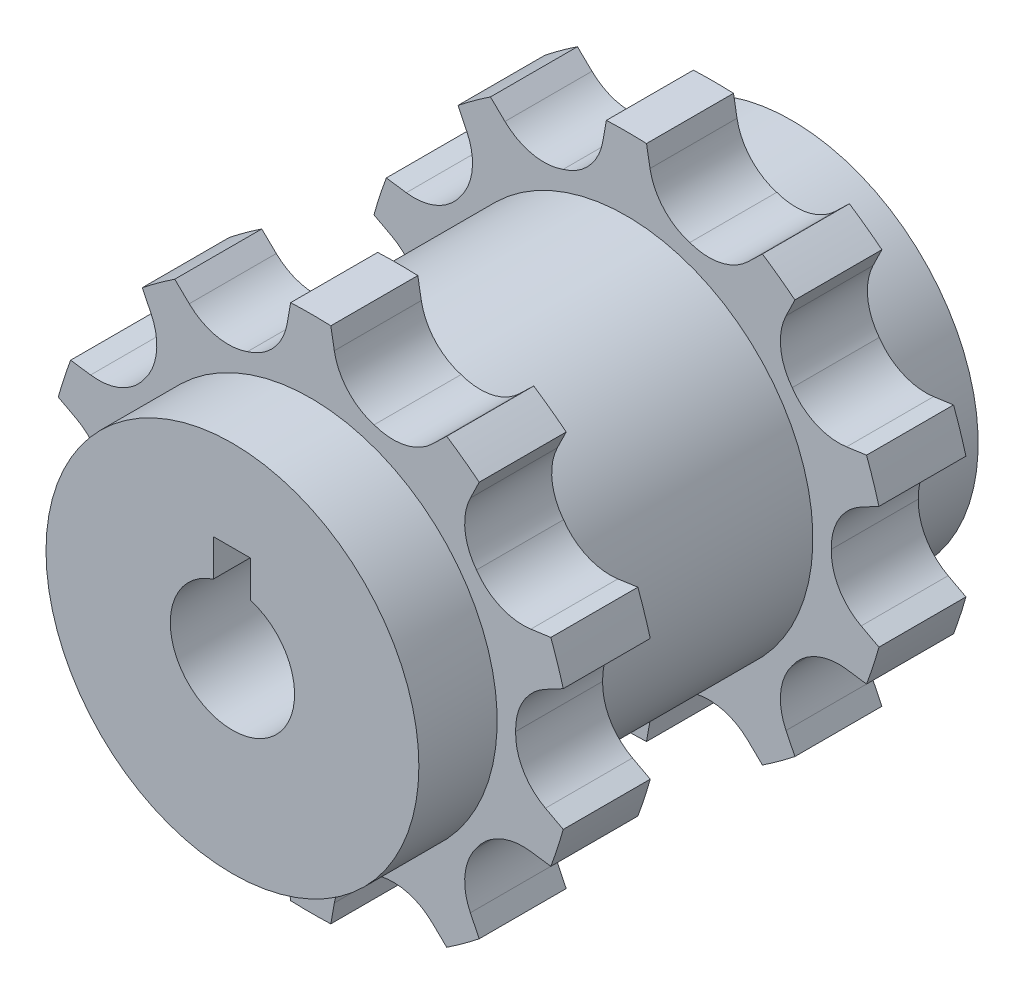
SolidWorks part; units mm, degrees
ref_plane "前视基准面" through (0, 0, 0) normal (0, 0, 1) x (1, 0, 0)
ref_plane "上视基准面" through (0, 0, 0) normal (0, 1, 0) x (1, 0, 0)
ref_plane "右视基准面" through (0, 0, 0) normal (1, 0, 0) x (0, 0, -1)
ref_plane "基准面4" through (0, 0, 28.9) normal (0, 0, 1) x (1, 0, 0)
sketch "草图1" plane through (0, 0, 28.9) normal (0, 0, 1) x (1, 0, 0)
  line L0 (42.4112, 45.7781) -> (42.1294, 47.3763)
  line L1 (38.8996, 47.3763) -> (38.6178, 45.7781)
  line L2 (30.741, 43.2187) -> (29.5736, 44.3461)
  line L3 (26.9607, 42.4477) -> (27.6721, 40.989)
  line L4 (22.804, 34.2886) -> (21.1969, 34.5145)
  line L5 (20.1988, 31.4428) -> (21.6317, 30.6809)
  line L6 (21.6317, 22.3988) -> (20.1988, 21.6369)
  line L7 (21.1969, 18.5652) -> (22.804, 18.791)
  line L8 (27.6721, 12.0906) -> (26.9607, 10.632)
  line L9 (29.5736, 8.7336) -> (30.741, 9.8609)
  line L10 (38.6178, 7.3016) -> (38.8996, 5.7034)
  line L11 (42.1294, 5.7034) -> (42.4112, 7.3016)
  line L12 (50.288, 9.8609) -> (51.4554, 8.7336)
  line L13 (54.0683, 10.632) -> (53.3569, 12.0906)
  line L14 (58.225, 18.791) -> (59.8321, 18.5652)
  line L15 (60.8302, 21.6369) -> (59.3973, 22.3988)
  line L16 (59.3973, 30.6809) -> (60.8302, 31.4428)
  line L17 (59.8321, 34.5145) -> (58.225, 34.2886)
  line L18 (53.3569, 40.989) -> (54.0683, 42.4477)
  line L19 (51.4554, 44.3461) -> (50.288, 43.2187)
  arc A0 (50.288, 43.2187) -> (45.609, 42.2191) centre (47.1467, 46.4716) cw
  arc A1 (45.609, 42.2191) -> (42.4112, 45.7781) centre (46.8645, 46.5633) cw
  arc A2 (42.1294, 47.3763) -> (38.8996, 47.3763) centre (40.5145, 8.5098) ccw
  arc A3 (38.6178, 45.7781) -> (35.42, 42.2191) centre (34.1645, 46.5633) cw
  arc A4 (35.42, 42.2191) -> (30.741, 43.2187) centre (33.8823, 46.4716) cw
  arc A5 (29.5736, 44.3461) -> (26.9607, 42.4477) centre (51.1123, 11.9533) ccw
  arc A6 (27.6721, 40.989) -> (27.1769, 36.2301) centre (23.6077, 39.0067) cw
  arc A7 (27.1769, 36.2301) -> (22.804, 34.2886) centre (23.4333, 38.7666) cw
  arc A8 (21.1969, 34.5145) -> (20.1988, 31.4428) centre (57.6621, 20.9683) ccw
  arc A9 (21.6317, 30.6809) -> (24.0284, 26.5398) centre (19.5088, 26.6882) cw
  arc A10 (24.0284, 26.5398) -> (21.6317, 22.3988) centre (19.5088, 26.3915) cw
  arc A11 (20.1988, 21.6369) -> (21.1969, 18.5652) centre (57.6621, 32.1114) ccw
  arc A12 (22.804, 18.791) -> (27.1769, 16.8495) centre (23.4333, 14.313) cw
  arc A13 (27.1769, 16.8495) -> (27.6721, 12.0906) centre (23.6077, 14.073) cw
  arc A14 (26.9607, 10.632) -> (29.5736, 8.7336) centre (51.1123, 41.1264) ccw
  arc A15 (30.741, 9.8609) -> (35.42, 10.8606) centre (33.8823, 6.6081) cw
  arc A16 (35.42, 10.8606) -> (38.6178, 7.3016) centre (34.1645, 6.5164) cw
  arc A17 (38.8996, 5.7034) -> (42.1294, 5.7034) centre (40.5145, 44.5698) ccw
  arc A18 (42.4112, 7.3016) -> (45.609, 10.8606) centre (46.8645, 6.5164) cw
  arc A19 (45.609, 10.8606) -> (50.288, 9.8609) centre (47.1467, 6.6081) cw
  arc A20 (51.4554, 8.7336) -> (54.0683, 10.632) centre (29.9167, 41.1264) ccw
  arc A21 (53.3569, 12.0906) -> (53.8521, 16.8495) centre (57.4213, 14.073) cw
  arc A22 (53.8521, 16.8495) -> (58.225, 18.791) centre (57.5957, 14.313) cw
  arc A23 (59.8321, 18.5652) -> (60.8302, 21.6369) centre (23.367, 32.1114) ccw
  arc A24 (59.3973, 22.3988) -> (57.0006, 26.5398) centre (61.5202, 26.3915) cw
  arc A25 (57.0006, 26.5398) -> (59.3973, 30.6809) centre (61.5202, 26.6882) cw
  arc A26 (60.8302, 31.4428) -> (59.8321, 34.5145) centre (23.367, 20.9683) ccw
  arc A27 (58.225, 34.2886) -> (53.8521, 36.2301) centre (57.5957, 38.7666) cw
  arc A28 (53.8521, 36.2301) -> (53.3569, 40.989) centre (57.4213, 39.0067) cw
  arc A29 (54.0683, 42.4477) -> (51.4554, 44.3461) centre (29.9167, 11.9533) ccw
extrude "凸台-拉伸1" add sketch "草图1" against normal blind 7
sketch "草图2" plane through (0, 0, 21.9) normal (0, 0, -1) x (-1, 0, 0)
  circle A0 centre (-40.5145, 26.5398) radius 15
extrude "凸台-拉伸2" add sketch "草图2" along normal blind 18.4
ref_plane "基准面5" through (0, 0, 3.5) normal (0, 0, 1) x (1, 0, 0)
sketch "草图3" plane through (0, 0, 3.5) normal (0, 0, 1) x (1, 0, 0)
  line L0 (42.4112, 45.7781) -> (42.1294, 47.3763)
  line L1 (38.8996, 47.3763) -> (38.6178, 45.7781)
  line L2 (30.741, 43.2187) -> (29.5736, 44.3461)
  line L3 (26.9607, 42.4477) -> (27.6721, 40.989)
  line L4 (22.804, 34.2886) -> (21.1969, 34.5145)
  line L5 (20.1988, 31.4428) -> (21.6317, 30.6809)
  line L6 (21.6317, 22.3988) -> (20.1988, 21.6369)
  line L7 (21.1969, 18.5652) -> (22.804, 18.791)
  line L8 (27.6721, 12.0906) -> (26.9607, 10.632)
  line L9 (29.5736, 8.7336) -> (30.741, 9.8609)
  line L10 (38.6178, 7.3016) -> (38.8996, 5.7034)
  line L11 (42.1294, 5.7034) -> (42.4112, 7.3016)
  line L12 (50.288, 9.8609) -> (51.4554, 8.7336)
  line L13 (54.0683, 10.632) -> (53.3569, 12.0906)
  line L14 (58.225, 18.791) -> (59.8321, 18.5652)
  line L15 (60.8302, 21.6369) -> (59.3973, 22.3988)
  line L16 (59.3973, 30.6809) -> (60.8302, 31.4428)
  line L17 (59.8321, 34.5145) -> (58.225, 34.2886)
  line L18 (53.3569, 40.989) -> (54.0683, 42.4477)
  line L19 (51.4554, 44.3461) -> (50.288, 43.2187)
  arc A0 (50.288, 43.2187) -> (45.609, 42.2191) centre (47.1467, 46.4716) cw
  arc A1 (45.609, 42.2191) -> (42.4112, 45.7781) centre (46.8645, 46.5633) cw
  arc A2 (42.1294, 47.3763) -> (38.8996, 47.3763) centre (40.5145, 8.5098) ccw
  arc A3 (38.6178, 45.7781) -> (35.42, 42.2191) centre (34.1645, 46.5633) cw
  arc A4 (35.42, 42.2191) -> (30.741, 43.2187) centre (33.8823, 46.4716) cw
  arc A5 (29.5736, 44.3461) -> (26.9607, 42.4477) centre (51.1123, 11.9533) ccw
  arc A6 (27.6721, 40.989) -> (27.1769, 36.2301) centre (23.6077, 39.0067) cw
  arc A7 (27.1769, 36.2301) -> (22.804, 34.2886) centre (23.4333, 38.7666) cw
  arc A8 (21.1969, 34.5145) -> (20.1988, 31.4428) centre (57.6621, 20.9683) ccw
  arc A9 (21.6317, 30.6809) -> (24.0284, 26.5398) centre (19.5088, 26.6882) cw
  arc A10 (24.0284, 26.5398) -> (21.6317, 22.3988) centre (19.5088, 26.3915) cw
  arc A11 (20.1988, 21.6369) -> (21.1969, 18.5652) centre (57.6621, 32.1114) ccw
  arc A12 (22.804, 18.791) -> (27.1769, 16.8495) centre (23.4333, 14.313) cw
  arc A13 (27.1769, 16.8495) -> (27.6721, 12.0906) centre (23.6077, 14.073) cw
  arc A14 (26.9607, 10.632) -> (29.5736, 8.7336) centre (51.1123, 41.1264) ccw
  arc A15 (30.741, 9.8609) -> (35.42, 10.8606) centre (33.8823, 6.6081) cw
  arc A16 (35.42, 10.8606) -> (38.6178, 7.3016) centre (34.1645, 6.5164) cw
  arc A17 (38.8996, 5.7034) -> (42.1294, 5.7034) centre (40.5145, 44.5698) ccw
  arc A18 (42.4112, 7.3016) -> (45.609, 10.8606) centre (46.8645, 6.5164) cw
  arc A19 (45.609, 10.8606) -> (50.288, 9.8609) centre (47.1467, 6.6081) cw
  arc A20 (51.4554, 8.7336) -> (54.0683, 10.632) centre (29.9167, 41.1264) ccw
  arc A21 (53.3569, 12.0906) -> (53.8521, 16.8495) centre (57.4213, 14.073) cw
  arc A22 (53.8521, 16.8495) -> (58.225, 18.791) centre (57.5957, 14.313) cw
  arc A23 (59.8321, 18.5652) -> (60.8302, 21.6369) centre (23.367, 32.1114) ccw
  arc A24 (59.3973, 22.3988) -> (57.0006, 26.5398) centre (61.5202, 26.3915) cw
  arc A25 (57.0006, 26.5398) -> (59.3973, 30.6809) centre (61.5202, 26.6882) cw
  arc A26 (60.8302, 31.4428) -> (59.8321, 34.5145) centre (23.367, 20.9683) ccw
  arc A27 (58.225, 34.2886) -> (53.8521, 36.2301) centre (57.5957, 38.7666) cw
  arc A28 (53.8521, 36.2301) -> (53.3569, 40.989) centre (57.4213, 39.0067) cw
  arc A29 (54.0683, 42.4477) -> (51.4554, 44.3461) centre (29.9167, 11.9533) ccw
extrude "凸台-拉伸3" add sketch "草图3" against normal blind 7
sketch "草图4" plane through (0, 0, 28.9) normal (0, 0, 1) x (1, 0, 0)
  circle A0 centre (40.5145, 26.5398) radius 15
extrude "凸台-拉伸4" add sketch "草图4" along normal blind 6.3
sketch "草图5" plane through (0, 0, -3.5) normal (0, 0, -1) x (-1, 0, 0)
  circle A0 centre (-40.5145, 26.5398) radius 15
extrude "凸台-拉伸5" add sketch "草图5" along normal blind 6.3
sketch "草图6" plane through (0, 0, -9.8) normal (0, 0, -1) x (-1, 0, 0)
  line L0 (-38.9718, 31.2959) -> (-38.9718, 34.2628)
  line L1 (-38.9718, 34.2628) -> (-41.9532, 34.2628)
  line L2 (-41.9532, 34.2628) -> (-41.9532, 31.3284)
  arc A0 (-41.9532, 31.3284) -> (-38.9718, 31.2959) centre (-40.5145, 26.5398) ccw
extrude "切除-拉伸1" cut sketch "草图6" against normal through all
